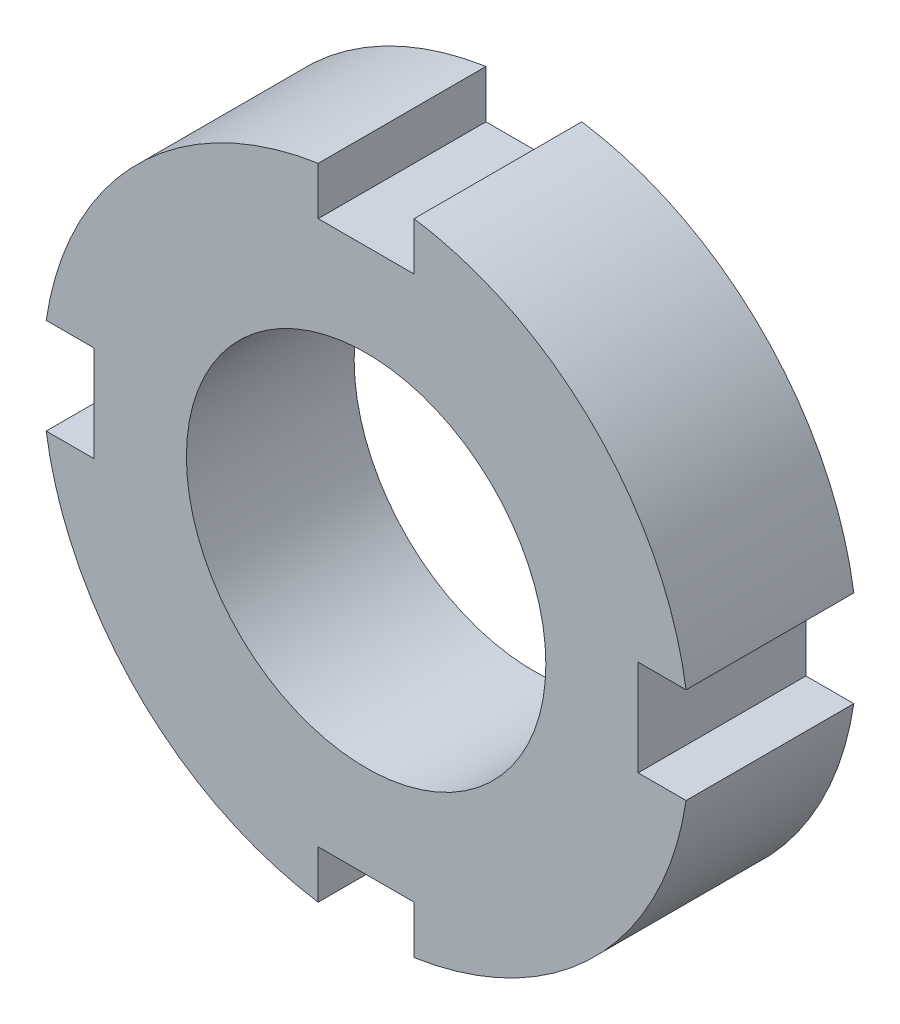
SolidWorks part; units mm, degrees
ref_plane "Plano frontal" through (0, 0, 0) normal (0, 0, 1) x (1, 0, 0)
ref_plane "Plano superior" through (0, 0, 0) normal (0, 1, 0) x (1, 0, 0)
ref_plane "Plano direito" through (0, 0, 0) normal (1, 0, 0) x (0, 0, -1)
sketch "Esboço1" plane through (0, 0, 0) normal (0, 0, 1) x (1, 0, 0)
  line L0 (0, 28.2078) -> (0, -26.6899) construction
  line L1 (-35.6872, 0) -> (36.9195, 0) construction
  line L2 (-2, 11.351) -> (2, 11.351)
  line L3 (2, 11.351) -> (2, 13.351)
  line L4 (-2, 11.351) -> (-2, 13.351)
  line L5 (11.351, 2) -> (11.351, -2)
  line L6 (11.351, -2) -> (13.351, -2)
  line L7 (11.351, 2) -> (13.351, 2)
  line L8 (2, -11.351) -> (2, -13.351)
  line L9 (-2, -11.351) -> (-2, -13.351)
  line L10 (-2, -11.351) -> (2, -11.351)
  line L11 (-11.351, -2) -> (-13.351, -2)
  line L12 (-11.351, 2) -> (-11.351, -2)
  line L13 (-11.351, 2) -> (-13.351, 2)
  circle A0 centre (0, 0) radius 7.5
  circle A1 centre (0, 0) radius 13.5
  point P7 (0, 25.8045)
  point P12 (0, 11.351)
  point P17 (11.351, 0)
  dimension "D1" = 27
  dimension "D2" = 15
  dimension "D3" = 4
  dimension "D4" = 2
extrude "Ressalto-extrusão1" add sketch "Esboço1" along normal blind 7 contours L7 A1 L3 L2 L4 L13 L12 L11 L9 L10 L8 L6 L5 A0
